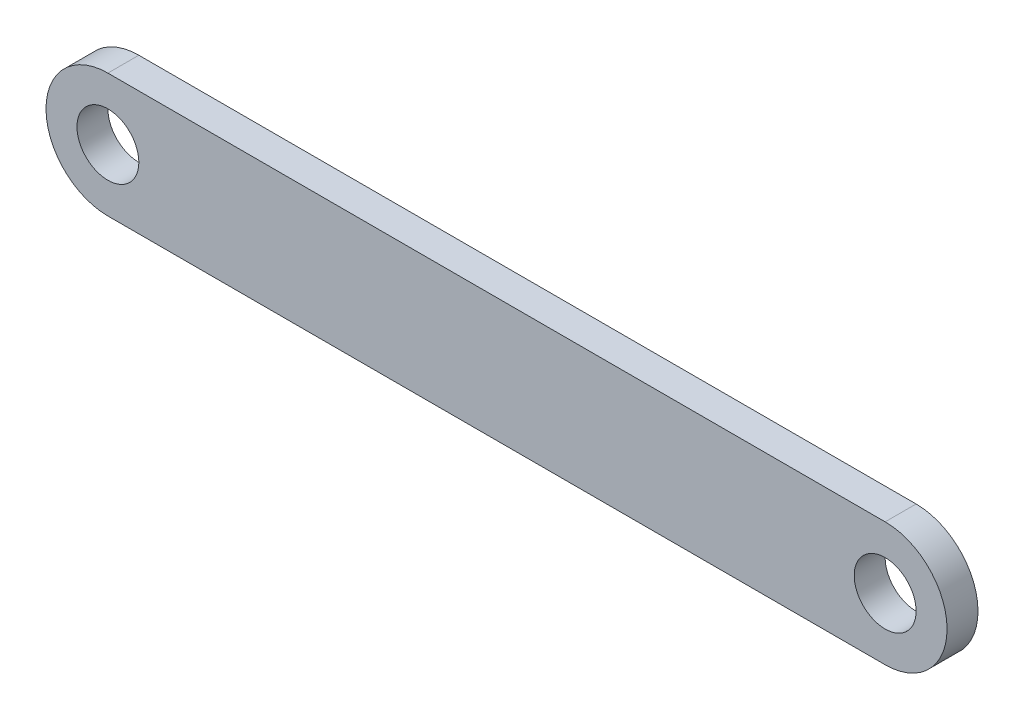
SolidWorks part; units mm, degrees
ref_plane "Спереди" through (0, 0, 0) normal (0, 0, 1) x (1, 0, 0)
ref_plane "Сверху" through (0, 0, 0) normal (0, 1, 0) x (1, 0, 0)
ref_plane "Справа" through (0, 0, 0) normal (1, 0, 0) x (0, 0, -1)
sketch "Sketch1" plane through (0, 0, 0) normal (0, 0, 1) x (1, 0, 0)
  line L0 (0, 0) -> (-25.1163, 0)
  line L1 (-25.1163, 2) -> (0, 2)
  line L2 (-25.1163, -2) -> (0, -2)
  circle A0 centre (0, 0) radius 1
  circle A1 centre (0, 0) radius 2
  circle A2 centre (-25.1163, 0) radius 1
  circle A3 centre (-25.1163, 0) radius 2
  point P12 (0, 0)
extrude "Extrude1" add sketch "Sketch1" along normal blind 1
